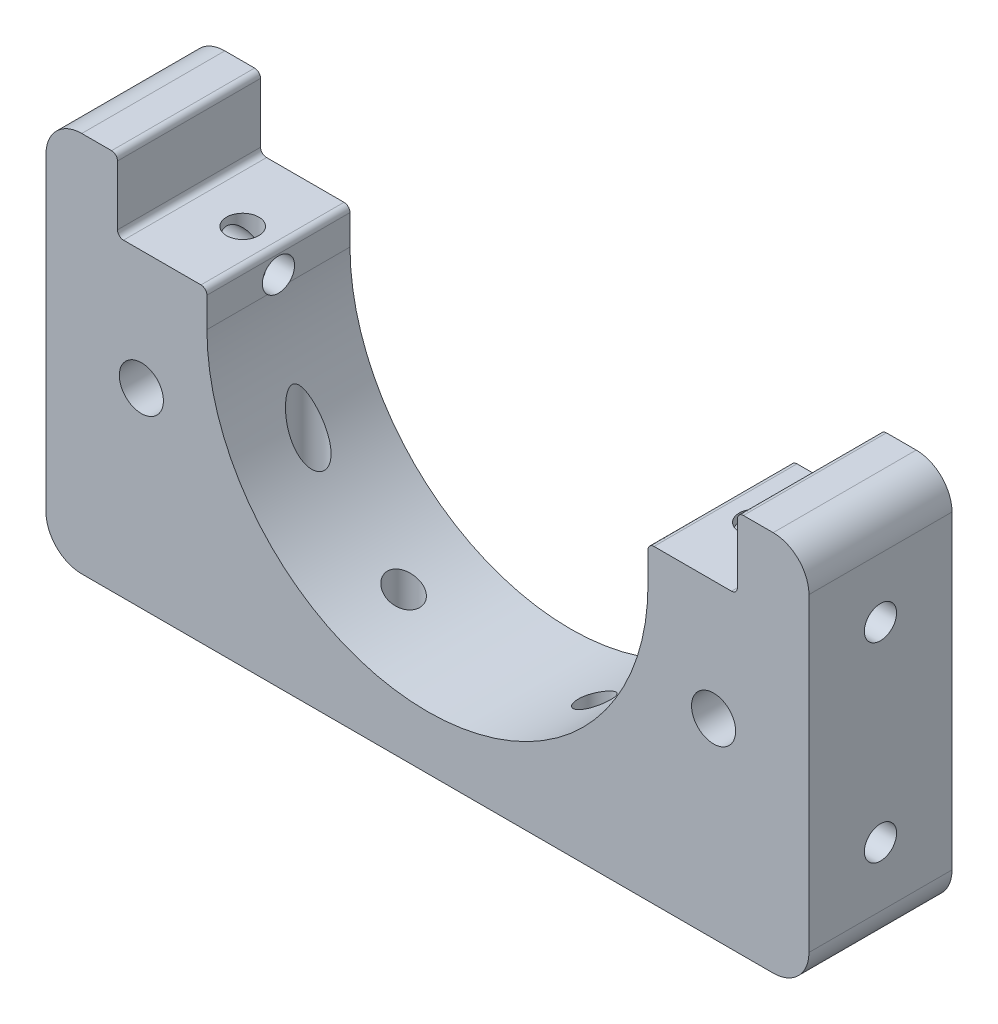
SolidWorks part; units mm, degrees
ref_plane "Front Plane" through (0, 0, 0) normal (0, 0, 1) x (1, 0, 0)
ref_plane "Top Plane" through (0, 0, 0) normal (0, 1, 0) x (1, 0, 0)
ref_plane "Right Plane" through (0, 0, 0) normal (1, 0, 0) x (0, 0, -1)
ref_plane "Plane1" through (0, 0, -6) normal (0, 0, -1) x (-1, 0, 0)
sketch "Sketch1" plane through (0, 0, -6) normal (0, 0, -1) x (-1, 0, 0)
  line L0 (32, -26) -> (32, 6)
  line L1 (32, 6) -> (-32, 6)
  line L2 (-32, 6) -> (-32, -26)
  line L3 (-32, -26) -> (32, -26)
extrude "Boss-Extrude1" add sketch "Sketch1" against normal blind 12
sketch "Sketch2" plane through (0, 0, 6) normal (0, 0, 1) x (1, 0, 0)
  line L0 (-26, 6) -> (-26, 0)
  line L1 (-26, 0) -> (-18.5, 0)
  line L2 (-18.5, 0) -> (-18.5, -3)
  line L3 (18.5, -3) -> (18.5, 6)
  line L4 (18.5, 6) -> (-26, 6)
  arc A0 (-18.5, -3) -> (18.5, -3) centre (0, -3) ccw
extrude "Cut-Extrude1" cut sketch "Sketch2" against normal through all
sketch "Sketch3" plane through (0, 0, 6) normal (0, 0, 1) x (1, 0, 0)
  line L0 (18.5, 0) -> (26, 0)
  line L1 (26, 0) -> (26, 6)
  line L2 (26, 6) -> (18.5, 6)
  line L3 (18.5, 6) -> (18.5, 0)
extrude "Cut-Extrude2" cut sketch "Sketch3" against normal through all
hole_wizard "M2.5 Clearance Hole1" positions "Sketch5" profile "Sketch4" hole size "M2.5" standard "ANSI Metric"
sketch "Sketch5" plane through (0, -26, 0) normal (0, -1, 0) x (-1, 0, 0)
  point P0 (8, 0)
  point P1 (-8, 0)
sketch "Sketch4" plane through (-8, -26, 0) normal (1, 0, 0) x (0, 0, -1)
  line L0 (0, 0) -> (0, 32)
  line L1 (0, 32) -> (1.3525, 32)
  line L2 (1.3525, 32) -> (1.3525, 0)
  line L5 (1.3525, 0) -> (0, 0)
  line L11 (0, -6.35) -> (0, 107.95) construction
  dimension "Thru Hole Dia." = 2.7051
  dimension "Thru Hole Depth" = 32
hole_wizard "M2.5 Clearance Hole2" positions "Sketch7" profile "Sketch6" hole size "M2.5" standard "ANSI Metric"
sketch "Sketch7" plane through (0, -26, 0) normal (0, -1, 0) x (-1, 0, 0)
  point P0 (16, 0)
  point P1 (-16, 0)
sketch "Sketch6" plane through (-16, -26, 0) normal (1, 0, 0) x (0, 0, -1)
  line L0 (0, 0) -> (0, 32)
  line L1 (0, 32) -> (1.3525, 32)
  line L2 (1.3525, 32) -> (1.3525, 0)
  line L5 (1.3525, 0) -> (0, 0)
  line L11 (0, -6.35) -> (0, 107.95) construction
  dimension "Thru Hole Dia." = 2.7051
  dimension "Thru Hole Depth" = 32
hole_wizard "Ø3.7 (3.7) Diameter Hole1" positions "Sketch9" profile "Sketch8" hole size "Ø3.7" standard "ANSI Metric"
sketch "Sketch9" plane through (0, 0, -6) normal (0, 0, -1) x (-1, 0, 0)
  point P0 (24, -10)
sketch "Sketch8" plane through (-24, -10, -6) normal (1, 0, 0) x (0, 1, 0)
  line L0 (0, 0) -> (0, 12)
  line L1 (0, 12) -> (1.85, 12)
  line L2 (1.85, 12) -> (1.85, 0)
  line L5 (1.85, 0) -> (0, 0)
  line L11 (0, -6.35) -> (0, 107.95) construction
  dimension "Thru Hole Dia." = 3.7
  dimension "Thru Hole Depth" = 12
hole_wizard "M2.5 Clearance Hole3" positions "Sketch11" profile "Sketch10" hole size "M2.5" standard "ANSI Metric"
sketch "Sketch11" plane through (0, 0, 0) normal (0, 1, 0) x (1, 0, 0)
  point P0 (21.5, 0)
  point P1 (-21.5, 0)
sketch "Sketch10" plane through (21.5, 0, 0) normal (1, 0, 0) x (0, 0, 1)
  line L0 (0, 0) -> (0, 12.5602)
  line L1 (0, 12.5602) -> (1.3525, 12)
  line L2 (1.3525, 12) -> (1.3525, 0)
  line L5 (1.3525, 0) -> (0, 0)
  line L10 (0, 12.5602) -> (-1.3525, 12) construction
  line L11 (0, -6.35) -> (0, 107.95) construction
  dimension "Hole Dia." = 2.7051
  dimension "Hole Depth" = 12
  dimension "Drill Angle" = 135
hole_wizard "Ø3.7 (3.7) Diameter Hole2" positions "Sketch13" profile "Sketch12" hole size "Ø3.7" standard "ANSI Metric"
sketch "Sketch13" plane through (0, 0, 6) normal (0, 0, 1) x (1, 0, 0)
  point P0 (24, -10)
sketch "Sketch12" plane through (24, -10, 6) normal (1, 0, 0) x (0, -1, 0)
  line L0 (0, 0) -> (0, 12)
  line L1 (0, 12) -> (1.85, 12)
  line L2 (1.85, 12) -> (1.85, 0)
  line L5 (1.85, 0) -> (0, 0)
  line L11 (0, -6.35) -> (0, 107.95) construction
  dimension "Thru Hole Dia." = 3.7
  dimension "Thru Hole Depth" = 12
hole_wizard "M2.5 Clearance Hole4" positions "Sketch15" profile "Sketch14" hole size "M2.5" standard "ANSI Metric"
sketch "Sketch15" plane through (32, 0, 0) normal (1, 0, 0) x (0, 0, -1)
  point P0 (0, -2)
sketch "Sketch14" plane through (32, -2, 0) normal (0, 1, 0) x (0, 0, -1)
  line L0 (0, 0) -> (0, 74.5)
  line L1 (0, 74.5) -> (1.3525, 74.5)
  line L2 (1.3525, 74.5) -> (1.3525, 0)
  line L5 (1.3525, 0) -> (0, 0)
  line L10 (0, 74.5) -> (-1.3526, 74.5) construction
  line L11 (0, -6.35) -> (0, 107.95) construction
  dimension "Hole Dia." = 2.7051
  dimension "Hole Depth" = 74.5
  dimension "Drill Angle" = 180
hole_wizard "M2.5 Clearance Hole5" positions "Sketch17" profile "Sketch16" hole size "M2.5" standard "ANSI Metric"
sketch "Sketch17" plane through (32, 0, 0) normal (1, 0, 0) x (0, 0, -1)
  point P0 (0, -18)
sketch "Sketch16" plane through (32, -18, 0) normal (0, 1, 0) x (0, 0, -1)
  line L0 (0, 0) -> (0, 11.0602)
  line L1 (0, 11.0602) -> (1.3525, 10.5)
  line L2 (1.3525, 10.5) -> (1.3525, 0)
  line L5 (1.3525, 0) -> (0, 0)
  line L10 (0, 11.0602) -> (-1.3525, 10.5) construction
  line L11 (0, -6.35) -> (0, 107.95) construction
  dimension "Hole Dia." = 2.7051
  dimension "Hole Depth" = 10.5
  dimension "Drill Angle" = 135
hole_wizard "M2.5 Clearance Hole6" positions "Sketch19" profile "Sketch18" hole size "M2.5" standard "ANSI Metric"
sketch "Sketch19" plane through (-32, 0, 0) normal (-1, 0, 0) x (0, 0, 1)
  point P0 (0, -18)
sketch "Sketch18" plane through (-32, -18, 0) normal (0, 1, 0) x (0, 0, 1)
  line L0 (0, 0) -> (0, 11.0602)
  line L1 (0, 11.0602) -> (1.3525, 10.5)
  line L2 (1.3525, 10.5) -> (1.3525, 0)
  line L5 (1.3525, 0) -> (0, 0)
  line L10 (0, 11.0602) -> (-1.3525, 10.5) construction
  line L11 (0, -6.35) -> (0, 107.95) construction
  dimension "Hole Dia." = 2.7051
  dimension "Hole Depth" = 10.5
  dimension "Drill Angle" = 135
fillet "Fillet1" radius 0.5 6 edges at (-18.5, 0, 0) (18.5, 0, 0) (26, 6, 0) (-26, 0, 0) (26, 0, 0) (-26, 6, 0)
fillet "Fillet2" radius 3 4 edges at (-32, 6, 0) (32, 6, 0) (-32, -26, 0) (32, -26, 0)
